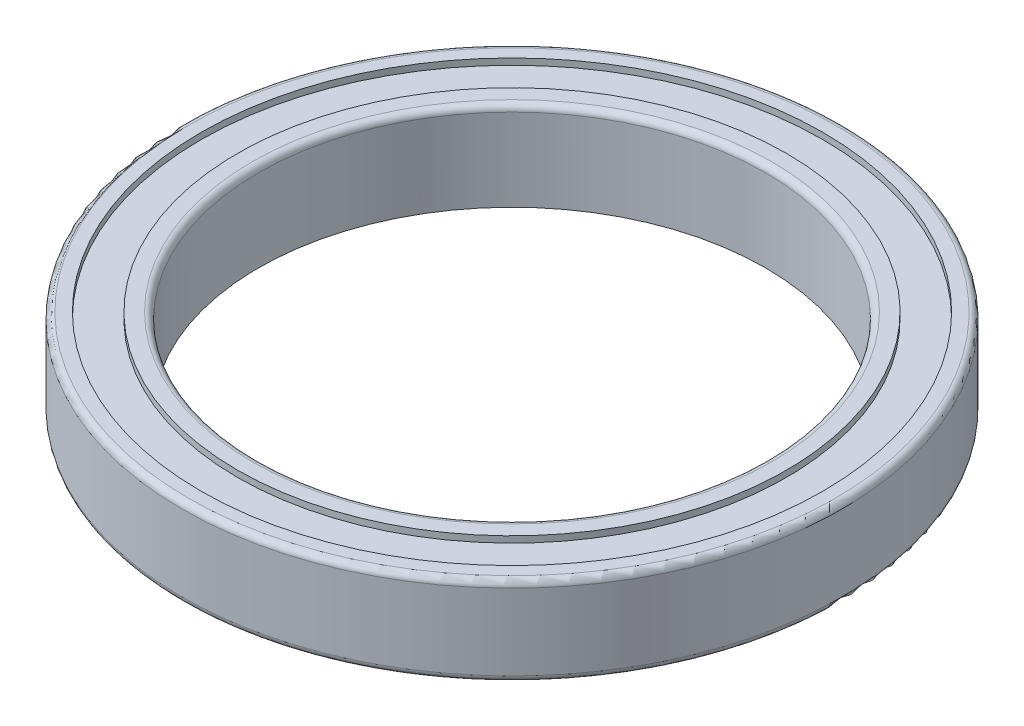
SolidWorks part; units mm, degrees
ref_plane "Ebene vorne" through (0, 0, 0) normal (0, 0, 1) x (1, 0, 0)
ref_plane "Ebene oben" through (0, 0, 0) normal (0, 1, 0) x (1, 0, 0)
ref_plane "Ebene rechts" through (0, 0, 0) normal (1, 0, 0) x (0, 0, -1)
sketch "Skizze1" plane through (0, 0, 0) normal (0, 0, 1) x (1, 0, 0)
  line L0 (0, 0) -> (0, 47.8414) construction
  line L1 (20, 0) -> (21.65, 0)
  line L2 (21.65, 0) -> (21.65, 0.5)
  line L3 (21.65, 0.5) -> (24.525, 0.5)
  line L4 (24.525, 0.5) -> (24.525, 0)
  line L5 (24.525, 0) -> (26, 0)
  line L6 (26, 0) -> (26, 7)
  line L7 (26, 7) -> (24.525, 7)
  line L8 (24.525, 7) -> (24.525, 6.5)
  line L9 (24.525, 6.5) -> (21.65, 6.5)
  line L10 (21.65, 6.5) -> (21.65, 7)
  line L11 (21.65, 7) -> (20, 7)
  line L12 (20, 7) -> (20, 0)
  point P15 (25.2625, 0)
  point P16 (25.2625, 7)
  dimension "D1" = 40
  dimension "D2" = 52
  dimension "D3" = 49.05
  dimension "D4" = 43.3
  dimension "D5" = 0.5
  dimension "D6" = 0.5
  dimension "D7" = 7
revolve "Rotation1" add sketch "Skizze1" angle 360 about L0
fillet "Verrundung1" radius 0.5 3 edges at (0, 0, -26) (0, 7, -26) (0, 7, -20)
